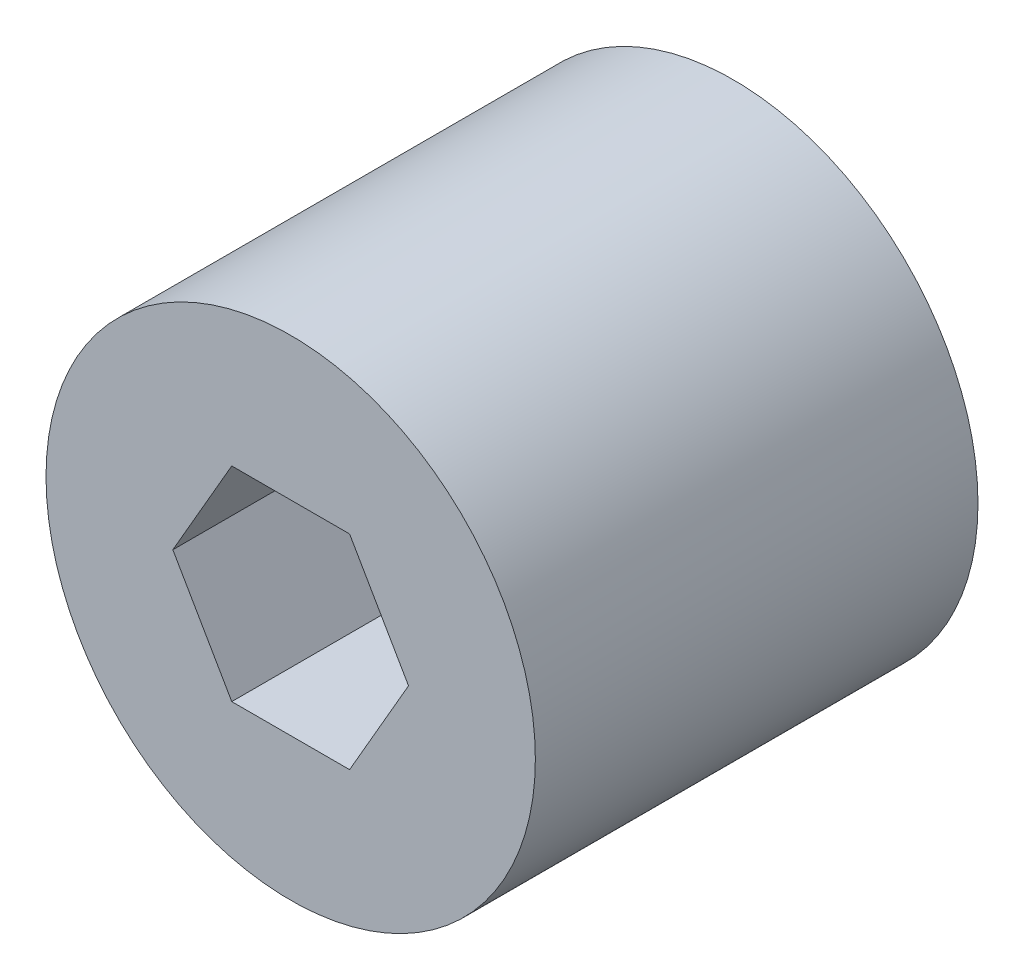
SolidWorks part; units mm, degrees
ref_plane "前视基准面" through (0, 0, 0) normal (0, 0, 1) x (1, 0, 0)
ref_plane "上视基准面" through (0, 0, 0) normal (0, 1, 0) x (1, 0, 0)
ref_plane "右视基准面" through (0, 0, 0) normal (1, 0, 0) x (0, 0, -1)
sketch "草图1" plane through (0, 0, 0) normal (0, 0, 1) x (1, 0, 0)
  circle A0 centre (0, 0) radius 4.975
  dimension "D1" = 9.95
extrude "凸台-拉伸1" add sketch "草图1" along normal blind 9
sketch "草图2" plane through (0, 0, 9) normal (0, 0, 1) x (1, 0, 0)
  line L1 (2.396, 0) -> (1.198, 2.075)
  line L2 (1.198, 2.075) -> (-1.198, 2.075)
  line L3 (-1.198, 2.075) -> (-2.396, 0)
  line L4 (-2.396, 0) -> (-1.198, -2.075)
  line L5 (-1.198, -2.075) -> (1.198, -2.075)
  line L6 (1.198, -2.075) -> (2.396, 0)
  circle A0 centre (0, 0) radius 2.075 construction
  dimension "D1" = 4.15
extrude "切除-拉伸1" cut sketch "草图2" against normal blind 7.5
